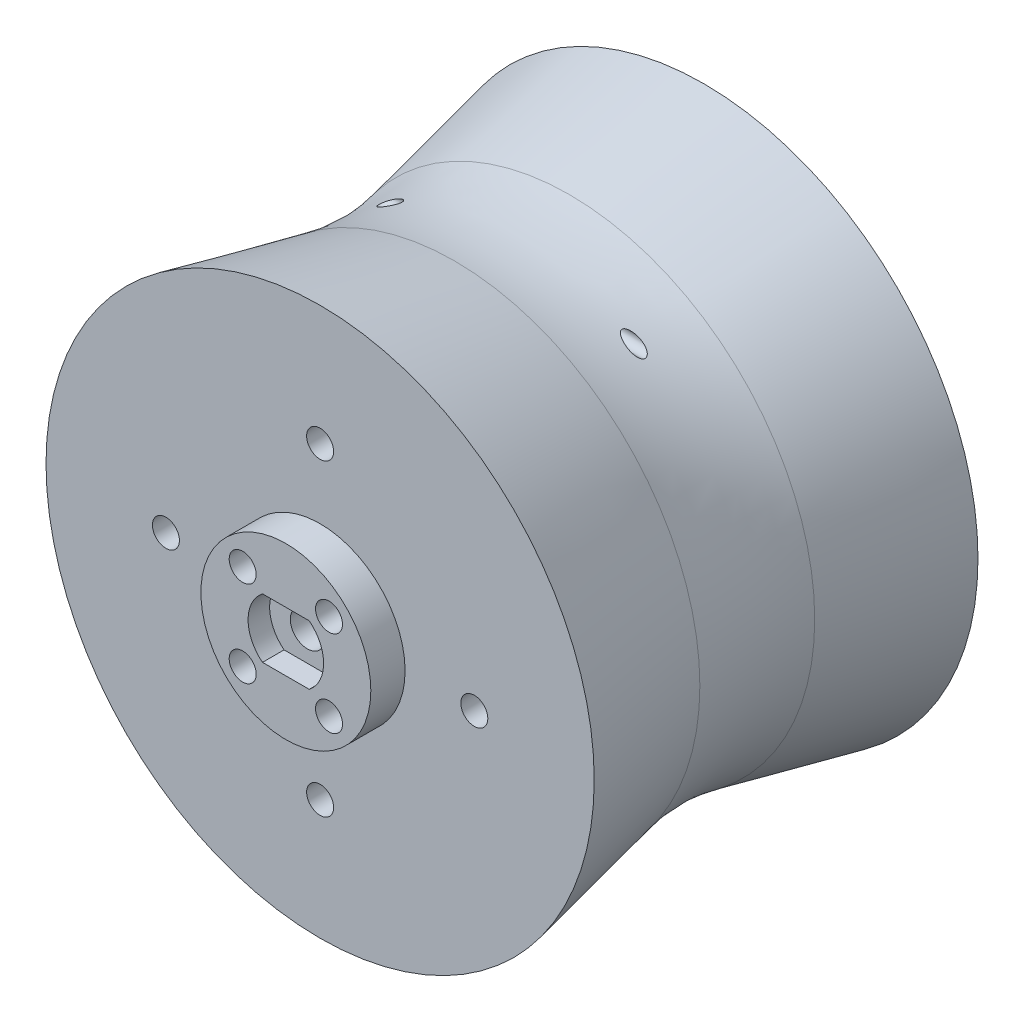
SolidWorks part; units mm, degrees
ref_plane "Front Plane" through (0, 0, 0) normal (0, 0, 1) x (1, 0, 0)
ref_plane "Top Plane" through (0, 0, 0) normal (0, 1, 0) x (1, 0, 0)
ref_plane "Right Plane" through (0, 0, 0) normal (1, 0, 0) x (0, 0, -1)
sketch "Sketch1" plane through (0, 0, 0) normal (0, 0, 1) x (1, 0, 0)
  circle A0 centre (0, 0) radius 50.8
  circle A1 centre (0, 0) radius 3.175
  dimension "D1" = 101.6
  dimension "D2" = 6.35
extrude "Boss-Extrude1" add sketch "Sketch1" along normal blind 71.12
sketch "Sketch2" plane through (0, 0, 0) normal (1, 0, 0) x (0, 0, -1)
  line L1 (39.116, 0) -> (-39.116, 0) construction
  line L2 (0, 55.88) -> (0, -55.88) construction
  circle A0 centre (-35.56, 38.1) radius 1.27
  dimension "D1" = 2.54
  dimension "D2" = 38.1
  dimension "D3" = 35.56
extrude "Cut-Extrude1" cut sketch "Sketch2" against normal through all both and the other way through all
sketch "Sketch7" plane through (0, 0, 0) normal (0, 0, -1) x (-1, 0, 0)
  line L0 (0, 28.575) -> (0, -28.575) construction
  line L1 (0, 42.6085) -> (0, -42.6085) construction
  line L2 (0, 28.575) -> (0, -28.575) construction
  line L3 (-28.575, 0) -> (28.575, 0) construction
  line L4 (42.6085, 0) -> (-42.6085, 0) construction
  line L5 (28.575, 0) -> (-28.575, 0) construction
  circle A0 centre (28.575, 0) radius 2.5
  circle A1 centre (0, 28.575) radius 2.5
  circle A2 centre (-28.575, 0) radius 2.5
  circle A3 centre (0, -28.575) radius 2.5
  point P7 (0, 0)
  point P14 (0, 0)
  dimension "D1" = 5
  dimension "D2" = 57.15
extrude "Cut-Extrude4" cut sketch "Sketch7" against normal blind 12.7
ref_plane "Plane1" through (0, 0, 35.56) normal (0, 0, 1) x (1, 0, 0)
mirror "Mirror1" about plane through (0, 0, 35.56) normal (0, 0, 1) of "Cut-Extrude4"
sketch "Sketch8" plane through (0, 0, 71.12) normal (0, 0, 1) x (1, 0, 0)
  circle A0 centre (0, 0) radius 15.748
  circle A1 centre (0, 0) radius 3.175 construction
  circle A2 centre (0, 0) radius 3.175
  dimension "D1" = 31.496
extrude "Boss-Extrude2" add sketch "Sketch8" along normal blind 6.35
sketch "Sketch5" plane through (0, 0, 77.47) normal (0, 0, 1) x (1, 0, 0)
  line L0 (-4.3301, 5.5) -> (4.3301, 5.5)
  line L1 (4.3301, -5.5) -> (-4.3301, -5.5)
  arc A0 (-4.3301, 5.5) -> (-4.3301, -5.5) centre (0, 0) ccw
  arc A1 (4.3301, -5.5) -> (4.3301, 5.5) centre (0, 0) ccw
  dimension "D1" = 14
  dimension "D2" = 5.5
  dimension "D3" = 11
sketch "Sketch6" plane through (0, 0, 77.47) normal (0, 0, 1) x (1, 0, 0)
  line L0 (0, 8) -> (0, -8) construction
  line L1 (-8, -8) -> (8, -8) construction
  line L3 (-8, 8) -> (8, 8) construction
  circle A4 centre (-8, 8) radius 2.5
  circle A6 centre (8, 8) radius 2.5
  circle A7 centre (8, -8) radius 2.5
  circle A9 centre (-8, -8) radius 2.5
  point P3 (0, 0)
  point P6 (0, -8)
  point P9 (0, 8)
  dimension "D1" = 5
  dimension "D2" = 16
  dimension "D3" = 16
extrude "Cut-Extrude6" cut sketch "Sketch5" against normal blind 4
extrude "Cut-Extrude7" cut sketch "Sketch6" against normal blind 7
ref_axis "Axis1" through (0, 0, -3.8735) along (0, 0, 1)
sketch "Sketch9" plane through (0, 0, 0) normal (1, 0, 0) x (0, 0, -1)
  line L0 (-71.12, 50.8) -> (-46.2041, 45.4609)
  line L1 (-24.9159, 45.4609) -> (0, 50.8)
  line L2 (0, 50.8) -> (-71.12, 50.8)
  line L3 (-35.56, 50.8) -> (-35.56, 43.18) construction
  line L4 (0, -50.8) -> (0, 50.8) construction
  arc A0 (-46.2041, 45.4609) -> (-24.9159, 45.4609) centre (-35.56, 95.1332) ccw
  dimension "D2" = 50.8
  dimension "D1" = 7.62
revolve "Cut-Revolve1" cut sketch "Sketch9" angle 360 about axis through (0, 0, -3.8735) along (0, 0, 1)
ref_plane "Plane2" through (0, 0, 35.56) normal (0, 0, -1) x (-1, 0, 0)
